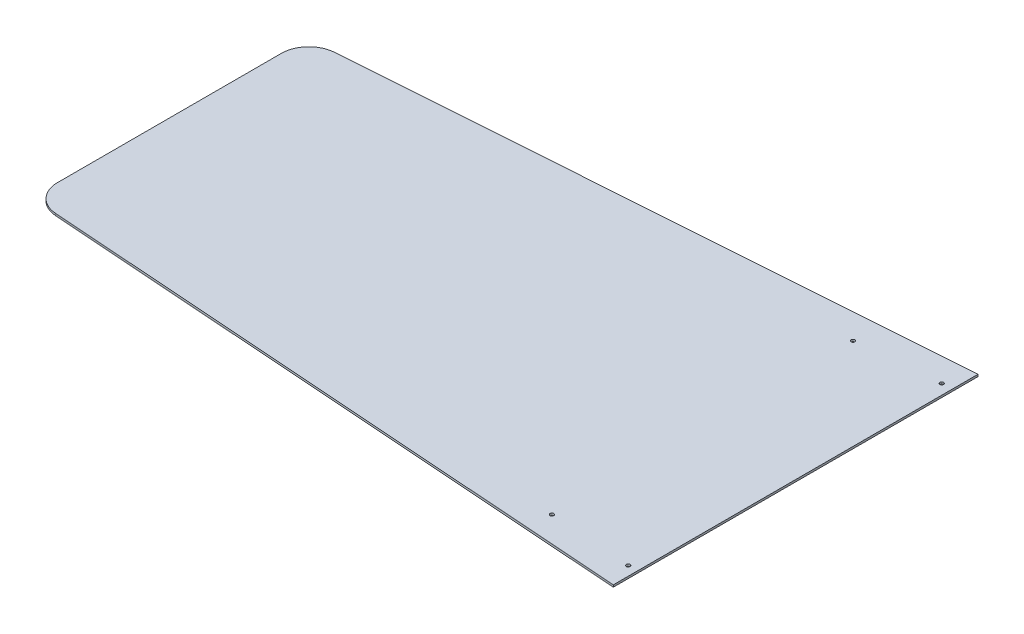
SolidWorks part; units mm, degrees
material "AISI 1010 Aço, barra laminada a quente"
ref_plane "Plano frontal" through (0, 0, 0) normal (0, 0, 1) x (1, 0, 0)
ref_plane "Plano superior" through (0, 0, 0) normal (0, 1, 0) x (1, 0, 0)
ref_plane "Plano direito" through (0, 0, 0) normal (1, 0, 0) x (0, 0, -1)
sketch "Esboço1" plane through (0, 0, 0) normal (0, 1, 0) x (1, 0, 0)
  line L0 (0, 162.7552) -> (0, -162.7552)
  line L1 (0, 0) -> (910, 0) construction
  line L2 (910, 265) -> (910, -265)
  line L3 (37.1501, 202.6536) -> (910, 265)
  line L4 (37.1501, -202.6536) -> (910, -265)
  arc A0 (0, 162.7552) -> (37.1501, 202.6536) centre (40, 162.7552) cw
  arc A1 (0, -162.7552) -> (37.1501, -202.6536) centre (40, -162.7552) ccw
  point P8 (910, 0)
  point P10 (0, 200)
  point P13 (0, -200)
  dimension "D4" = 40
  dimension "D1" = 400
  dimension "D2" = 910
  dimension "D3" = 530
extrude "Ressalto-extrusão1" add sketch "Esboço1" along normal blind 3
sketch "Sketch1" plane through (0, 3, 0) normal (0, 1, 0) x (1, 0, 0)
  circle A0 centre (776.9986, -221.1374) radius 2.75
  circle A1 centre (896.4055, -229.7712) radius 2.75
  circle A2 centre (776.9986, 216.2599) radius 2.75
  circle A3 centre (895.0618, 227.274) radius 2.75
  dimension "D1" = 5.5
extrude "Cut-Extrude1" cut sketch "Sketch1" against normal blind 10
